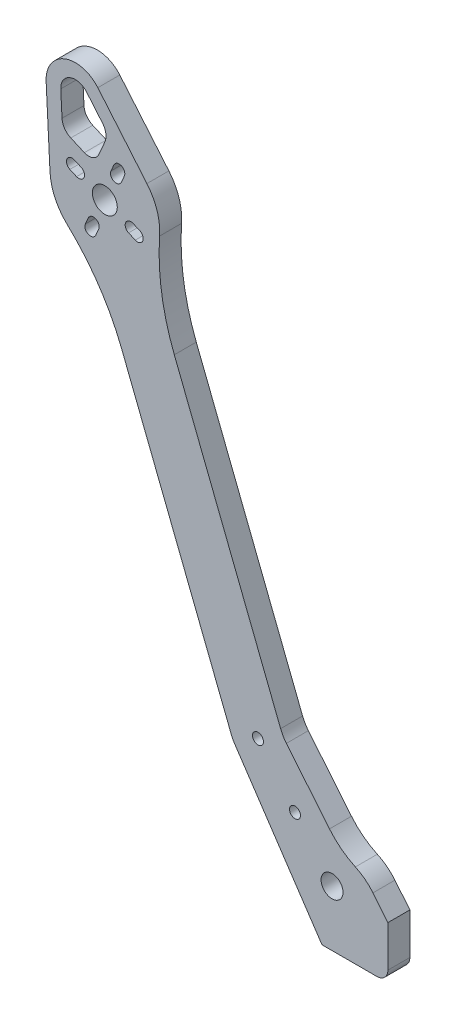
SolidWorks part; units mm, degrees
ref_plane "Alzado" through (0, 0, 0) normal (0, 0, 1) x (1, 0, 0)
ref_plane "Planta" through (0, 0, 0) normal (0, 1, 0) x (1, 0, 0)
ref_plane "Vista lateral" through (0, 0, 0) normal (1, 0, 0) x (0, 0, -1)
sketch "Croquis1" plane through (0, 0, 0) normal (0, 0, 1) x (1, 0, 0)
  line L0 (-29.3036, 45.4733) -> (-58.3369, 119.3899)
  line L2 (-71.9944, 154.8181) -> (-72.7937, 152.9848)
  line L3 (-41.9317, 35.7196) -> (-18, 0)
  line L4 (-15.9491, 28.4359) -> (-27.7258, 42.7852)
  line L5 (-86.8687, 148.9757) -> (-85.0354, 148.1764)
  line L6 (-67.7548, 144.0243) -> (-69.5881, 144.8236)
  line L7 (-68.9937, 141.1826) -> (-70.827, 141.9819)
  line L8 (-79.2262, 172.119) -> (-65.8206, 156.1412)
  line L9 (-42.7067, 37.1999) -> (-72.7639, 113.7232)
  line L10 (-82.8978, 154.9193) -> (-86.6114, 156.5383)
  line L11 (0, 14.25) -> (0, 3)
  line L12 (0, 14.25) -> (-4.0797, 19.2447)
  line L13 (-89.3497, 166.7753) -> (-89.0077, 160.0032)
  line L14 (-18, 0) -> (-3, 0)
  line L15 (-93.3446, 166.5735) -> (-92.2927, 145.7434)
  line L16 (-78.9489, 156.4704) -> (-77.3298, 160.184)
  line L17 (-77.9268, 164.3471) -> (-82.2905, 169.5481)
  line L18 (-74.8361, 156.057) -> (-75.6354, 154.2236)
  line L19 (-85.6298, 151.8174) -> (-83.7965, 151.0181)
  line L20 (-82.6291, 138.1819) -> (-81.8298, 140.0152)
  line L21 (-79.7874, 136.943) -> (-78.9881, 138.7764)
  arc A0 (-77.3298, 160.184) -> (-77.9268, 164.3471) centre (-80.9965, 161.7826) ccw
  arc A1 (-71.9944, 154.8181) -> (-74.8361, 156.057) centre (-73.4152, 155.4375) ccw
  arc A2 (-82.6291, 138.1819) -> (-79.7874, 136.943) centre (-81.2081, 137.5628) ccw
  arc A3 (-3, 0) -> (0, 3) centre (-3, 3) ccw
  arc A4 (-69.5881, 144.8236) -> (-70.827, 141.9819) centre (-70.2072, 143.4026) ccw
  arc A5 (-85.6298, 151.8174) -> (-86.8687, 148.9757) centre (-86.2489, 150.3964) ccw
  arc A6 (-15.9491, 28.4359) -> (-8.887, 22.9726) centre (-0.4892, 41.1241) ccw
  circle A7 centre (-77.3117, 146.5) radius 3.4
  arc A8 (-79.2262, 172.119) -> (-93.3446, 166.5735) centre (-85.3548, 166.977) ccw
  circle A9 centre (-15.25, 15.25) radius 3
  arc A10 (-68.9937, 141.1826) -> (-67.7548, 144.0243) centre (-68.3742, 142.6035) ccw
  arc A11 (-85.0354, 148.1764) -> (-83.7965, 151.0181) centre (-84.4159, 149.5972) ccw
  arc A12 (-29.3036, 45.4733) -> (-27.7258, 42.7852) centre (-19.9959, 49.1293) ccw
  arc A13 (-82.8978, 154.9193) -> (-78.9489, 156.4704) centre (-81.6989, 157.6693) ccw
  circle A14 centre (-25.3716, 27.6416) radius 1.5
  arc A15 (-75.6354, 154.2236) -> (-72.7937, 152.9848) centre (-74.2143, 153.6046) ccw
  arc A16 (-92.2927, 145.7434) -> (-87.5715, 135.5575) centre (-77.3117, 146.5) ccw
  arc A17 (-42.7067, 37.1999) -> (-41.9317, 35.7196) centre (-35.4932, 40.0333) ccw
  arc A18 (-82.2905, 169.5481) -> (-89.3497, 166.7753) centre (-85.3548, 166.977) ccw
  arc A19 (-4.0797, 19.2447) -> (-8.887, 22.9726) centre (-14.5796, 10.6683) ccw
  arc A20 (-72.7639, 113.7232) -> (-87.5715, 135.5575) centre (-128.6104, 91.7876) ccw
  arc A21 (-62.3475, 145.4651) -> (-58.3369, 119.3899) centre (-2.4905, 141.3256) ccw
  arc A22 (-62.3475, 145.4651) -> (-65.8206, 156.1412) centre (-77.3117, 146.5) ccw
  arc A23 (-78.9881, 138.7764) -> (-81.8298, 140.0152) centre (-80.409, 139.3958) ccw
  arc A24 (-89.0077, 160.0032) -> (-86.6114, 156.5383) centre (-85.0128, 160.205) ccw
  circle A25 centre (-35.4932, 40.0333) radius 1.5
extrude "Saliente-Extruir1" add sketch "Croquis1" along normal blind 6
